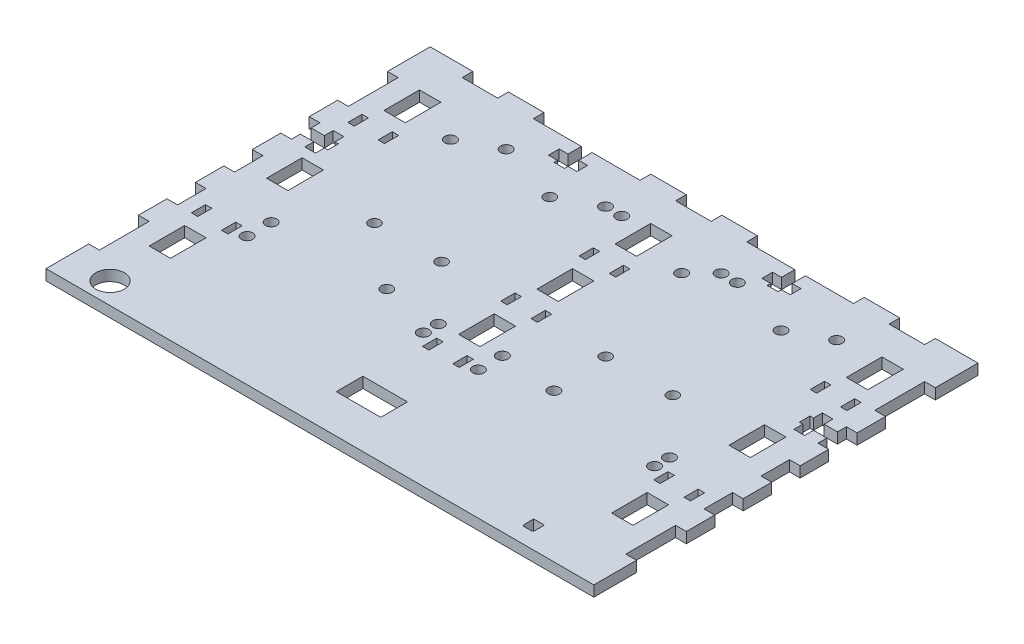
SolidWorks part; units mm, degrees
material "Balsa"
ref_plane "Alzado" through (0, 0, 0) normal (0, 0, 1) x (1, 0, 0)
ref_plane "Planta" through (0, 0, 0) normal (0, 1, 0) x (1, 0, 0)
ref_plane "Vista lateral" through (0, 0, 0) normal (1, 0, 0) x (0, 0, -1)
sketch "Croquis1" plane through (0, 0, 0) normal (0, 1, 0) x (1, 0, 0)
  line L0 (-77, 0) -> (-74, 0) construction
  line L1 (-77, -54) -> (77, -54)
  line L2 (-77, -54) -> (-77, 54)
  line L3 (-77, 54) -> (77, 54)
  line L4 (77, -54) -> (77, 54)
  line L5 (-77, -54) -> (77, 54) construction
  line L6 (-77, 54) -> (77, -54) construction
  line L7 (0, -54) -> (0, 54) construction
  line L8 (-74, 54) -> (-74, -54) construction
  line L9 (-77, -42) -> (-74, -42)
  line L10 (-77, 4) -> (-74, 4)
  line L11 (-77, 4) -> (-77, -4)
  line L12 (-77, -4) -> (-74, -4)
  line L13 (-74, 4) -> (-74, -4)
  line L14 (-77, 12) -> (-74, 12)
  line L15 (-77, 12) -> (-77, 20)
  line L16 (-77, 20) -> (-74, 20)
  line L17 (-74, 12) -> (-74, 20)
  line L22 (-77, 28) -> (-74, 28)
  line L23 (-77, 28) -> (-77, 42)
  line L24 (-77, 42) -> (-74, 42)
  line L25 (-74, 28) -> (-74, 42)
  line L26 (-74, -28) -> (-74, -42)
  line L27 (-77, -28) -> (-74, -28)
  line L28 (-77, -28) -> (-77, -42)
  line L29 (-77, -20) -> (-74, -20)
  line L30 (-74, -12) -> (-74, -20)
  line L31 (-77, -12) -> (-74, -12)
  line L32 (-77, -12) -> (-77, -20)
  line L33 (77, 42) -> (74, 42)
  line L34 (74, 28) -> (74, 42)
  line L35 (77, 28) -> (74, 28)
  line L36 (77, 28) -> (77, 42)
  line L37 (77, -28) -> (77, -42)
  line L38 (77, -28) -> (74, -28)
  line L39 (74, -28) -> (74, -42)
  line L40 (77, -42) -> (74, -42)
  line L41 (77, -12) -> (77, -20)
  line L42 (77, -12) -> (74, -12)
  line L43 (74, -12) -> (74, -20)
  line L44 (77, -20) -> (74, -20)
  line L45 (77, 20) -> (74, 20)
  line L46 (74, 12) -> (74, 20)
  line L47 (77, 12) -> (74, 12)
  line L48 (77, 12) -> (77, 20)
  line L49 (77, -4) -> (74, -4)
  line L50 (74, 4) -> (74, -4)
  line L51 (77, 4) -> (74, 4)
  line L52 (77, 4) -> (77, -4)
  line L53 (-77, 51) -> (77, 51) construction
  line L54 (-55, 51) -> (-65, 51)
  line L55 (-5, 54) -> (5, 54)
  line L56 (-5, 54) -> (-5, 51)
  line L57 (-5, 51) -> (5, 51)
  line L58 (5, 54) -> (5, 51)
  line L59 (15, 54) -> (45, 54)
  line L60 (15, 54) -> (15, 51)
  line L61 (15, 51) -> (45, 51)
  line L62 (45, 54) -> (45, 51)
  line L63 (55, 54) -> (65, 54)
  line L64 (55, 54) -> (55, 51)
  line L65 (55, 51) -> (65, 51)
  line L66 (65, 54) -> (65, 51)
  line L67 (-65, 54) -> (-65, 51)
  line L68 (-55, 54) -> (-65, 54)
  line L69 (-55, 54) -> (-55, 51)
  line L70 (-15, 51) -> (-45, 51)
  line L71 (-45, 54) -> (-45, 51)
  line L72 (-15, 54) -> (-45, 54)
  line L73 (-15, 54) -> (-15, 51)
  line L74 (-77, -48) -> (77, -48) construction
  line L75 (-30, 51) -> (-30, 10.4132) construction
  line L76 (53, -49.6) -> (55, -49.6)
  line L77 (52.5, -49.1) -> (52.5, -46.4)
  line L78 (52.5, -46.4) -> (55.5, -46.4)
  line L79 (55.5, -49.1) -> (55.5, -46.4)
  line L80 (52.5, -49.6) -> (55.5, -46.4) construction
  line L81 (52.5, -46.4) -> (55.5, -49.6) construction
  line L83 (-74, 1.5) -> (-74, -1.5)
  line L90 (-31.5, 51) -> (-28.5, 51)
  line L91 (-31.5, 51) -> (-31.5, 43.27)
  line L92 (-31.5, 43.27) -> (-28.5, 43.27)
  line L93 (-28.5, 51) -> (-28.5, 43.27)
  line L94 (-34, 47.25) -> (-26, 47.25)
  line L95 (-34, 47.25) -> (-34, 44.25)
  line L96 (-34, 44.25) -> (-26, 44.25)
  line L97 (-26, 47.25) -> (-26, 44.25)
  line L98 (31.5, 43.27) -> (28.5, 43.27)
  line L99 (28.5, 51) -> (28.5, 43.27)
  line L100 (31.5, 51) -> (28.5, 51)
  line L101 (31.5, 51) -> (31.5, 43.27)
  line L102 (34, 44.25) -> (26, 44.25)
  line L103 (26, 47.25) -> (26, 44.25)
  line L104 (34, 47.25) -> (26, 47.25)
  line L105 (34, 47.25) -> (34, 44.25)
  line L109 (74, 1.5) -> (74, -1.5)
  line L114 (-74, 16) -> (74, 16) construction
  line L115 (70.25, 12) -> (67.25, 12)
  line L116 (-74, 14.5) -> (-66.27, 14.5)
  line L117 (-74, 14.5) -> (-74, 17.5)
  line L118 (-74, 17.5) -> (-66.27, 17.5)
  line L119 (-66.27, 14.5) -> (-66.27, 17.5)
  line L120 (-70.25, 20) -> (-67.25, 20)
  line L121 (-70.25, 20) -> (-70.25, 12)
  line L122 (-70.25, 12) -> (-67.25, 12)
  line L123 (-67.25, 20) -> (-67.25, 12)
  line L124 (67.25, 20) -> (67.25, 12)
  line L125 (70.25, 20) -> (67.25, 20)
  line L126 (70.25, 20) -> (70.25, 12)
  line L127 (74, 17.5) -> (66.27, 17.5)
  line L128 (66.27, 14.5) -> (66.27, 17.5)
  line L129 (74, 14.5) -> (66.27, 14.5)
  line L130 (74, 14.5) -> (74, 17.5)
  line L131 (74, 0) -> (77, 0) construction
  circle A0 centre (-65, -48) radius 4
  arc A1 (55.5, -49.1) -> (55, -49.6) centre (55, -49.1) cw
  arc A2 (53, -49.6) -> (52.5, -49.1) centre (53, -49.1) cw
  point P0 (0, 0)
  point P78 (54, -48)
  point P123 (-75.5, 4)
  dimension "D17" = 8
  dimension "D22" = 0.5
  dimension "D1" = 108
  dimension "D2" = 154
  dimension "D3" = 3
  dimension "D4" = 4
  dimension "D5" = 3
  dimension "D6" = 8
  dimension "D7" = 8
  dimension "D8" = 8
  dimension "D9" = 14
  dimension "D10" = 3
  dimension "D11" = 5
  dimension "D12" = 10
  dimension "D13" = 10
  dimension "D14" = 30
  dimension "D15" = 10
  dimension "D16" = 10
  dimension "D18" = 6
  dimension "D19" = 23
  dimension "D20" = 3.2
  dimension "D21" = 3
  dimension "D23" = 12
  dimension "D31" = 3
  dimension "D32" = 8
  dimension "D33" = 1.5
  dimension "D34" = 4
  dimension "D35" = 0.98
  dimension "D36" = 7.73
  dimension "D37" = 8
  dimension "D38" = 3
  dimension "D39" = 1.5
  dimension "D40" = 0.98
  dimension "D41" = 8
  dimension "D42" = 4
  dimension "D43" = 3
  dimension "D44" = 7.73
extrude "Saliente-Extruir1" add sketch "Croquis1" along normal mid plane 3
sketch "Croquis2" plane through (0, 1.5, 0) normal (0, 1, 0) x (1, 0, 0)
  line L0 (-4.25, 26) -> (4.25, 26) construction
  line L17 (3, 15) -> (8.9055, 15) construction
  line L18 (-60.75, -18) -> (-69.25, -18) construction
  line L19 (-3, 42) -> (3, 42)
  line L20 (-3, 42) -> (-3, 32)
  line L21 (-3, 32) -> (3, 32)
  line L22 (3, 42) -> (3, 32)
  line L35 (-3, 20) -> (-3, 10)
  line L36 (-3, 20) -> (3, 20)
  line L37 (3, 20) -> (3, 10)
  line L38 (-3, 10) -> (3, 10)
  line L39 (-3, -2) -> (-3, -12)
  line L40 (-3, -2) -> (3, -2)
  line L41 (3, -2) -> (3, -12)
  line L42 (-3, -12) -> (3, -12)
  line L43 (0, -12) -> (0, 42) construction
  line L44 (3.35, 24) -> (5.15, 24)
  line L45 (3.35, 24) -> (3.35, 28)
  line L62 (77, 42) -> (77, 54) construction
  line L63 (62, 42) -> (68, 42)
  line L64 (62, 42) -> (62, 32)
  line L65 (62, 32) -> (68, 32)
  line L66 (68, 42) -> (68, 32)
  line L67 (3.35, 28) -> (5.15, 28)
  line L84 (0, 0) -> (0, -8.6841) construction
  line L93 (-62, 32) -> (-68, 32)
  line L94 (-68, 42) -> (-68, 32)
  line L95 (-62, 42) -> (-68, 42)
  line L96 (-62, 42) -> (-62, 32)
  line L97 (77, 42) -> (74, 42) construction
  line L98 (5.15, 24) -> (5.15, 28)
  line L99 (3.35, 24) -> (5.15, 28) construction
  line L100 (3.35, 28) -> (5.15, 24) construction
  line L101 (-3.35, 24) -> (-5.15, 24)
  line L102 (-3.35, 24) -> (-3.35, 28)
  line L103 (-3.35, 28) -> (-5.15, 28)
  line L104 (-5.15, 24) -> (-5.15, 28)
  line L105 (-3.35, 24) -> (-5.15, 28) construction
  line L106 (-3.35, 28) -> (-5.15, 24) construction
  line L107 (-3.35, 2) -> (-5.15, 6) construction
  line L108 (-3.35, 6) -> (-5.15, 2) construction
  line L109 (3.35, 2) -> (5.15, 6) construction
  line L110 (3.35, 6) -> (5.15, 2) construction
  line L111 (-4.25, 4) -> (4.25, 4) construction
  line L112 (-5.15, 6) -> (-5.15, 2)
  line L113 (-3.35, 2) -> (-5.15, 2)
  line L114 (-3.35, 6) -> (-3.35, 2)
  line L115 (-3.35, 6) -> (-5.15, 6)
  line L116 (5.15, 6) -> (5.15, 2)
  line L117 (3.35, 2) -> (5.15, 2)
  line L118 (3.35, 6) -> (3.35, 2)
  line L119 (3.35, 6) -> (5.15, 6)
  line L120 (3, -7) -> (13.1268, -7) construction
  line L121 (-4.25, -18) -> (4.25, -18) construction
  line L122 (3.35, -20) -> (5.15, -16) construction
  line L123 (3.35, -16) -> (5.15, -20) construction
  line L124 (-3.35, -20) -> (-5.15, -16) construction
  line L125 (-3.35, -16) -> (-5.15, -20) construction
  line L126 (3.35, -20) -> (5.15, -20)
  line L127 (3.35, -20) -> (3.35, -16)
  line L128 (3.35, -16) -> (5.15, -16)
  line L129 (5.15, -20) -> (5.15, -16)
  line L130 (-3.35, -20) -> (-5.15, -20)
  line L131 (-3.35, -20) -> (-3.35, -16)
  line L132 (-3.35, -16) -> (-5.15, -16)
  line L133 (-5.15, -20) -> (-5.15, -16)
  line L134 (-62, 37) -> (-3, 37) construction
  line L135 (-3, 37) -> (3, 37) construction
  line L136 (3, 37) -> (62, 37) construction
  line L137 (-32.5, 37) -> (-32.5, -41.0641) construction
  line L138 (-61.65, 28) -> (-59.85, 24) construction
  line L139 (-61.65, 24) -> (-59.85, 28) construction
  line L140 (-68.35, 28) -> (-70.15, 24) construction
  line L141 (-68.35, 24) -> (-70.15, 28) construction
  line L142 (-65, -12) -> (-65, 42) construction
  line L143 (-60.75, 26) -> (-69.25, 26) construction
  line L144 (-59.85, 24) -> (-59.85, 28)
  line L145 (-61.65, 28) -> (-59.85, 28)
  line L146 (-61.65, 24) -> (-61.65, 28)
  line L147 (-61.65, 24) -> (-59.85, 24)
  line L148 (-70.15, 24) -> (-70.15, 28)
  line L149 (-68.35, 28) -> (-70.15, 28)
  line L150 (-68.35, 24) -> (-68.35, 28)
  line L151 (-68.35, 24) -> (-70.15, 24)
  line L152 (60.75, 26) -> (69.25, 26) construction
  line L153 (65, -12) -> (65, 42) construction
  line L154 (68.35, 24) -> (70.15, 28) construction
  line L155 (68.35, 28) -> (70.15, 24) construction
  line L156 (61.65, 24) -> (59.85, 28) construction
  line L157 (61.65, 28) -> (59.85, 24) construction
  line L158 (68.35, 24) -> (70.15, 24)
  line L159 (68.35, 24) -> (68.35, 28)
  line L160 (68.35, 28) -> (70.15, 28)
  line L161 (70.15, 24) -> (70.15, 28)
  line L162 (61.65, 24) -> (59.85, 24)
  line L163 (61.65, 24) -> (61.65, 28)
  line L164 (61.65, 28) -> (59.85, 28)
  line L165 (59.85, 24) -> (59.85, 28)
  line L166 (-4.25, 4) -> (-65, 4) construction
  line L167 (-3, -7) -> (-65, -7) construction
  line L168 (-68, -1) -> (-62, -1)
  line L169 (-68, -1) -> (-68, 9)
  line L170 (-68, 9) -> (-62, 9)
  line L171 (-62, -1) -> (-62, 9)
  line L172 (-68, -1) -> (-62, 9) construction
  line L173 (-68, 9) -> (-62, -1) construction
  line L174 (61.65, -20) -> (59.85, -16) construction
  line L179 (61.65, -16) -> (59.85, -20) construction
  line L180 (68.35, -20) -> (70.15, -16) construction
  line L181 (68.35, -16) -> (70.15, -20) construction
  line L186 (-68.35, -16) -> (-70.15, -20) construction
  line L187 (-68.35, -20) -> (-70.15, -16) construction
  line L188 (-61.65, -16) -> (-59.85, -20) construction
  line L189 (-61.65, -20) -> (-59.85, -16) construction
  line L190 (-68.35, -16) -> (-70.15, -16)
  line L191 (-68.35, -16) -> (-68.35, -20)
  line L192 (-68.35, -20) -> (-70.15, -20)
  line L193 (-70.15, -16) -> (-70.15, -20)
  line L194 (-61.65, -16) -> (-59.85, -16)
  line L195 (-61.65, -16) -> (-61.65, -20)
  line L196 (-61.65, -20) -> (-59.85, -20)
  line L197 (-59.85, -16) -> (-59.85, -20)
  line L198 (-62, -34) -> (-62, -24)
  line L199 (-62, -34) -> (-68, -34)
  line L200 (-68, -34) -> (-68, -24)
  line L201 (-62, -24) -> (-68, -24)
  line L202 (68, 9) -> (62, -1) construction
  line L203 (68, -1) -> (62, 9) construction
  line L204 (60.75, -18) -> (69.25, -18) construction
  line L205 (62, -24) -> (68, -24)
  line L206 (68, -34) -> (68, -24)
  line L207 (62, -34) -> (68, -34)
  line L208 (62, -34) -> (62, -24)
  line L209 (59.85, -16) -> (59.85, -20)
  line L210 (61.65, -20) -> (59.85, -20)
  line L211 (61.65, -16) -> (61.65, -20)
  line L212 (61.65, -16) -> (59.85, -16)
  line L213 (70.15, -16) -> (70.15, -20)
  line L214 (68.35, -20) -> (70.15, -20)
  line L215 (68.35, -16) -> (68.35, -20)
  line L216 (68.35, -16) -> (70.15, -16)
  line L217 (62, -1) -> (62, 9)
  line L218 (68, 9) -> (62, 9)
  line L219 (68, -1) -> (68, 9)
  line L220 (68, -1) -> (62, -1)
  point P9 (0, 26)
  point P39 (0, 4)
  point P53 (0, -18)
  point P78 (-65, 26)
  point P92 (65, 26)
  point P132 (-65, -18)
  point P140 (65, -18)
  dimension "D10" = 4
  dimension "D2" = 0
  dimension "D4" = 0
  dimension "D5" = 6
  dimension "D6" = 8.5
  dimension "D7" = 3
  dimension "D8" = 1.8
  dimension "D9" = 1.8
  dimension "D11" = 4
  dimension "D12" = 6
  dimension "D13" = 12
  dimension "D14" = 10
  dimension "D15" = 10
  dimension "D16" = 6
  dimension "D34" = 6
  dimension "D35" = 10
  dimension "D36" = 9
extrude "Cortar-Extruir1" cut sketch "Croquis2" against normal blind 3
sketch "Croquis3" plane through (0, 1.5, 0) normal (0, 1, 0) x (1, 0, 0)
  line L0 (52.5, -46.4) -> (0, -46.4) construction
  line L1 (0, -46.4) -> (0, -39.4) construction
  line L3 (-6.25, -43.15) -> (6.25, -43.15)
  line L4 (-6.25, -43.15) -> (-6.25, -35.65)
  line L5 (-6.25, -35.65) -> (6.25, -35.65)
  line L6 (6.25, -43.15) -> (6.25, -35.65)
  line L7 (-6.25, -43.15) -> (6.25, -35.65) construction
  line L8 (-6.25, -35.65) -> (6.25, -43.15) construction
  dimension "D1" = 7.5
  dimension "D2" = 12.5
  dimension "D3" = 7
extrude "Cortar-Extruir2" cut sketch "Croquis3" against normal blind 10
sketch "Croquis4" plane through (0, 1.5, 0) normal (0, 1, 0) x (1, 0, 0)
  circle A0 centre (-41.39, 39.73) radius 1.5875
  circle A1 centre (-13.45, 39.73) radius 1.5875
  circle A2 centre (51.55, 39.73) radius 1.5875
  circle A3 centre (23.61, 39.73) radius 1.5875
  circle A4 centre (56.63, -12.34) radius 1.5875
  circle A5 centre (8.37, -11.07) radius 1.5875
  circle A6 centre (-8.37, -12.34) radius 1.5875
  circle A7 centre (-56.63, -11.07) radius 1.5875
  circle A8 centre (-24.13, -11.07) radius 1.5875
  circle A9 centre (24.13, -12.34) radius 1.5875
  circle A10 centre (19.05, 39.73) radius 1.5875
  circle A11 centre (-8.89, 39.73) radius 1.5875
extrude "Cortar-Extruir3" cut sketch "Croquis4" against normal blind 10
sketch "Croquis5" plane through (0, 1.5, 0) normal (0, 1, 0) x (1, 0, 0)
  line L0 (-5.15, -18) -> (-59.85, -18) construction
  line L1 (-53, 41.27) -> (-12, 41.27) construction
  line L2 (-53, 41.27) -> (-53, -34.73) construction
  line L3 (-53, -34.73) -> (-12, -34.73) construction
  line L4 (-12, 41.27) -> (-12, -34.73) construction
  line L5 (-53, 41.27) -> (-12, -34.73) construction
  line L6 (-53, -34.73) -> (-12, 41.27) construction
  line L7 (-5.15, -16) -> (-5.15, -20) construction
  line L8 (-59.85, -20) -> (-59.85, -16) construction
  line L9 (-32.5, -18) -> (-32.5, 43.27) construction
  line L10 (-32.5, 43.27) -> (-31.5, 43.27) construction
  line L11 (-31.5, 43.27) -> (-28.5, 43.27) construction
  line L12 (-41.925, 3.27) -> (-23.075, 3.27) construction
  line L13 (0, 0) -> (0, 17.3029) construction
  line L14 (41.925, 3.27) -> (23.075, 3.27) construction
  circle A0 centre (-41.925, 3.27) radius 1.55
  circle A1 centre (-23.075, 3.27) radius 1.55
  circle A2 centre (23.075, 3.27) radius 1.55
  circle A3 centre (41.925, 3.27) radius 1.55
  point P0 (-32.5, 3.27)
  point P19 (-30, 43.27)
  point P23 (-32.5, 3.27)
  point P30 (32.5, 3.27)
  dimension "D5" = 3.1
  dimension "D1" = 76
  dimension "D2" = 41
  dimension "D3" = 2
  dimension "D4" = 18.85
extrude "Cortar-Extruir4" cut sketch "Croquis5" against normal blind 10
sketch "Croquis6" plane through (0, -1.5, 0) normal (0, -1, 0) x (1, 0, 0)
  circle A0 centre (-51.55, -34.24) radius 1.5875
  circle A1 centre (-23.61, -34.24) radius 1.5748
  circle A2 centre (13.45, -34.24) radius 1.5875
  circle A3 centre (41.39, -34.24) radius 1.5875
  circle A4 centre (56.63, 16.56) radius 1.5875
  circle A5 centre (8.37, 17.83) radius 1.5875
  circle A6 centre (-56.63, 17.83) radius 1.5875
  circle A7 centre (-8.37, 16.56) radius 1.5875
extrude "Cortar-Extruir5" cut sketch "Croquis6" against normal blind 10
sketch "Croquis7" plane through (0, 1.5, 0) normal (0, 1, 0) x (1, 0, 0)
  line L0 (-65, 32) -> (-65, 42) construction
  line L3 (-68, 32) -> (-62, 32) construction
  line L4 (-62, 42) -> (-68, 42) construction
  line L5 (-4.9598, 37.15) -> (4.9598, 37.15)
  line L6 (-69.9598, 36.85) -> (-60.0402, 36.85)
  line L7 (-69.9598, 36.85) -> (-69.9598, 37.15)
  line L8 (-69.9598, 37.15) -> (-60.0402, 37.15)
  line L9 (-60.0402, 36.85) -> (-60.0402, 37.15)
  line L10 (-69.9598, 36.85) -> (-60.0402, 37.15) construction
  line L11 (-69.9598, 37.15) -> (-60.0402, 36.85) construction
  line L12 (-65.15, 30.0862) -> (-64.85, 30.0862)
  line L13 (-65.15, 30.0862) -> (-65.15, 43.9138)
  line L14 (-65.15, 43.9138) -> (-64.85, 43.9138)
  line L15 (-64.85, 30.0862) -> (-64.85, 43.9138)
  line L16 (-65.15, 30.0862) -> (-64.85, 43.9138) construction
  line L17 (-65.15, 43.9138) -> (-64.85, 30.0862) construction
  line L18 (-4.9598, 36.85) -> (4.9598, 36.85)
  line L19 (-0.15, 30.0862) -> (-0.15, 43.9138)
  line L20 (0.15, 30.0862) -> (0.15, 43.9138)
  line L21 (60.0402, 37.15) -> (69.9598, 37.15)
  line L22 (60.0402, 36.85) -> (69.9598, 36.85)
  line L23 (64.85, 30.0862) -> (64.85, 43.9138)
  line L24 (65.15, 30.0862) -> (65.15, 43.9138)
  line L25 (-4.9598, 15.15) -> (4.9598, 15.15)
  line L26 (-4.9598, 14.85) -> (4.9598, 14.85)
  line L27 (-0.15, 8.0862) -> (-0.15, 21.9138)
  line L28 (0.15, 8.0862) -> (0.15, 21.9138)
  line L29 (-69.7947, 4.4135) -> (-59.8752, 4.4135)
  line L30 (-69.7947, 4.1135) -> (-59.8752, 4.1135)
  line L31 (-64.985, -2.6503) -> (-64.985, 11.1773)
  line L32 (-64.685, -2.6503) -> (-64.685, 11.1773)
  line L33 (-4.9598, -6.85) -> (4.9598, -6.85)
  line L34 (-4.9598, -7.15) -> (4.9598, -7.15)
  line L35 (-0.15, -13.9138) -> (-0.15, -0.0862)
  line L36 (0.15, -13.9138) -> (0.15, -0.0862)
  line L37 (59.6021, 4.0258) -> (69.5216, 4.0258)
  line L38 (59.6021, 3.7258) -> (69.5216, 3.7258)
  line L39 (64.4118, -3.038) -> (64.4118, 10.7896)
  line L40 (64.7118, -3.038) -> (64.7118, 10.7896)
  line L45 (60.0402, -28.85) -> (69.9598, -28.85)
  line L46 (60.0402, -29.15) -> (69.9598, -29.15)
  line L47 (64.85, -35.9138) -> (64.85, -22.0862)
  line L48 (65.15, -35.9138) -> (65.15, -22.0862)
  line L57 (-69.9598, -28.85) -> (-60.0402, -28.85)
  line L58 (-69.9598, -29.15) -> (-60.0402, -29.15)
  line L59 (-65.15, -35.9138) -> (-65.15, -22.0862)
  line L60 (-64.85, -35.9138) -> (-64.85, -22.0862)
  line L61 (-69.9598, 15.15) -> (-60.0402, 15.15)
  line L62 (-69.9598, 14.85) -> (-60.0402, 14.85)
  line L63 (-65.15, 8.0862) -> (-65.15, 21.9138)
  line L64 (-64.85, 8.0862) -> (-64.85, 21.9138)
  line L65 (-69.9598, -6.85) -> (-60.0402, -6.85)
  line L66 (-69.9598, -7.15) -> (-60.0402, -7.15)
  line L67 (-65.15, -13.9138) -> (-65.15, -0.0862)
  line L68 (-64.85, -13.9138) -> (-64.85, -0.0862)
  line L69 (-4.9598, -28.85) -> (4.9598, -28.85)
  line L70 (-4.9598, -29.15) -> (4.9598, -29.15)
  line L71 (-0.15, -35.9138) -> (-0.15, -22.0862)
  line L72 (0.15, -35.9138) -> (0.15, -22.0862)
  line L73 (60.0402, 15.15) -> (69.9598, 15.15)
  line L74 (60.0402, 14.85) -> (69.9598, 14.85)
  line L75 (64.85, 8.0862) -> (64.85, 21.9138)
  line L76 (65.15, 8.0862) -> (65.15, 21.9138)
  line L77 (60.0402, -6.85) -> (69.9598, -6.85)
  line L78 (60.0402, -7.15) -> (69.9598, -7.15)
  line L79 (64.85, -13.9138) -> (64.85, -0.0862)
  line L80 (65.15, -13.9138) -> (65.15, -0.0862)
  point P6 (-65, 37)
  point P11 (-65, 37)
  dimension "D1" = 0.3
  dimension "D2" = 0.3
  dimension "D3" = 3
  dimension "D4" = 4
sketch "Croquis8" plane through (0, 1.5, 0) normal (0, 1, 0) x (1, 0, 0)
  line L0 (-60.9976, 22.6864) -> (-60.9976, 25.9114)
  line L2 (-69.4235, 22.5308) -> (-69.4235, 25.7558)
  line L4 (-69.1235, 22.5308) -> (-69.1235, 25.7558)
  line L5 (-6.6732, 26.0558) -> (-4.4235, 26.0558)
  line L6 (-69.1235, 25.7558) -> (-66.8737, 25.7558)
  line L7 (-71.6732, 25.7558) -> (-69.4235, 25.7558)
  line L9 (-71.6732, 26.0558) -> (-69.4235, 26.0558)
  line L11 (-6.6732, 25.7558) -> (-4.4235, 25.7558)
  line L12 (-4.4235, 26.0558) -> (-4.4235, 29.2808)
  line L13 (-60.6976, 22.6864) -> (-60.6976, 25.9114)
  line L14 (-69.4235, 26.0558) -> (-69.4235, 29.2808)
  line L15 (-60.6976, 25.9114) -> (-58.4479, 25.9114)
  line L16 (-63.2474, 25.9114) -> (-60.9976, 25.9114)
  line L17 (-63.2474, 26.2114) -> (-60.9976, 26.2114)
  line L18 (-4.1235, 26.0558) -> (-4.1235, 29.2808)
  line L20 (-60.9976, 26.052) -> (-60.9976, 26.0708)
  line L21 (-69.1235, 26.0558) -> (-69.1235, 29.2808)
  line L22 (-60.6976, 26.052) -> (-60.6976, 26.0708)
  line L23 (-60.6976, 26.2114) -> (-60.6976, 29.4364)
  line L24 (-60.9976, 26.2114) -> (-60.9976, 29.4364)
  line L25 (-60.6976, 26.2114) -> (-58.4479, 26.2114)
  line L26 (-69.1235, 26.0558) -> (-66.8737, 26.0558)
  line L28 (-4.1235, 26.0558) -> (-1.8737, 26.0558)
  line L29 (-4.1235, 25.7558) -> (-1.8737, 25.7558)
  line L30 (-4.1235, 22.5308) -> (-4.1235, 25.7558)
  line L31 (-4.4235, 22.5308) -> (-4.4235, 25.7558)
  line L32 (1.7526, 26.2114) -> (4.0024, 26.2114)
  line L33 (1.7526, 25.9114) -> (4.0024, 25.9114)
  line L34 (4.0024, 26.2114) -> (4.0024, 29.4364)
  line L35 (4.3024, 26.2114) -> (4.3024, 29.4364)
  line L36 (4.3024, 26.2114) -> (6.5521, 26.2114)
  line L37 (4.3024, 25.9114) -> (6.5521, 25.9114)
  line L38 (4.3024, 22.6864) -> (4.3024, 25.9114)
  line L39 (4.0024, 22.6864) -> (4.0024, 25.9114)
  line L40 (58.3268, 26.0558) -> (60.5765, 26.0558)
  line L41 (58.3268, 25.7558) -> (60.5765, 25.7558)
  line L42 (60.5765, 26.0558) -> (60.5765, 29.2808)
  line L43 (60.8765, 26.0558) -> (60.8765, 29.2808)
  line L44 (60.8765, 26.0558) -> (63.1263, 26.0558)
  line L45 (60.8765, 25.7558) -> (63.1263, 25.7558)
  line L46 (60.8765, 22.5308) -> (60.8765, 25.7558)
  line L47 (60.5765, 22.5308) -> (60.5765, 25.7558)
  line L48 (66.7526, 26.2114) -> (69.0024, 26.2114)
  line L49 (66.7526, 25.9114) -> (69.0024, 25.9114)
  line L50 (69.0024, 26.2114) -> (69.0024, 29.4364)
  line L51 (69.3024, 26.2114) -> (69.3024, 29.4364)
  line L52 (69.3024, 26.2114) -> (71.5521, 26.2114)
  line L53 (69.3024, 25.9114) -> (71.5521, 25.9114)
  line L54 (69.3024, 22.6864) -> (69.3024, 25.9114)
  line L55 (69.0024, 22.6864) -> (69.0024, 25.9114)
  line L56 (-6.6732, 4.0558) -> (-4.4235, 4.0558)
  line L57 (-6.6732, 3.7558) -> (-4.4235, 3.7558)
  line L58 (-4.4235, 4.0558) -> (-4.4235, 7.2808)
  line L59 (-4.1235, 4.0558) -> (-4.1235, 7.2808)
  line L60 (-4.1235, 4.0558) -> (-1.8737, 4.0558)
  line L61 (-4.1235, 3.7558) -> (-1.8737, 3.7558)
  line L62 (-4.1235, 0.5308) -> (-4.1235, 3.7558)
  line L63 (-4.4235, 0.5308) -> (-4.4235, 3.7558)
  line L64 (1.7526, 4.2114) -> (4.0024, 4.2114)
  line L65 (1.7526, 3.9114) -> (4.0024, 3.9114)
  line L66 (4.0024, 4.2114) -> (4.0024, 7.4364)
  line L67 (4.3024, 4.2114) -> (4.3024, 7.4364)
  line L68 (4.3024, 4.2114) -> (6.5521, 4.2114)
  line L69 (4.3024, 3.9114) -> (6.5521, 3.9114)
  line L70 (4.3024, 0.6864) -> (4.3024, 3.9114)
  line L71 (4.0024, 0.6864) -> (4.0024, 3.9114)
  line L88 (-6.6732, -17.9442) -> (-4.4235, -17.9442)
  line L89 (-6.6732, -18.2442) -> (-4.4235, -18.2442)
  line L90 (-4.4235, -17.9442) -> (-4.4235, -14.7192)
  line L91 (-4.1235, -17.9442) -> (-4.1235, -14.7192)
  line L92 (-4.1235, -17.9442) -> (-1.8737, -17.9442)
  line L93 (-4.1235, -18.2442) -> (-1.8737, -18.2442)
  line L94 (-4.1235, -21.4692) -> (-4.1235, -18.2442)
  line L95 (-4.4235, -21.4692) -> (-4.4235, -18.2442)
  line L96 (1.7526, -17.7886) -> (4.0024, -17.7886)
  line L97 (1.7526, -18.0886) -> (4.0024, -18.0886)
  line L98 (4.0024, -17.7886) -> (4.0024, -14.5636)
  line L99 (4.3024, -17.7886) -> (4.3024, -14.5636)
  line L100 (4.3024, -17.7886) -> (6.5521, -17.7886)
  line L101 (4.3024, -18.0886) -> (6.5521, -18.0886)
  line L102 (4.3024, -21.3136) -> (4.3024, -18.0886)
  line L103 (4.0024, -21.3136) -> (4.0024, -18.0886)
  line L104 (58.3268, -17.9442) -> (60.5765, -17.9442)
  line L105 (58.3268, -18.2442) -> (60.5765, -18.2442)
  line L106 (60.5765, -17.9442) -> (60.5765, -14.7192)
  line L107 (60.8765, -17.9442) -> (60.8765, -14.7192)
  line L108 (60.8765, -17.9442) -> (63.1263, -17.9442)
  line L109 (60.8765, -18.2442) -> (63.1263, -18.2442)
  line L110 (60.8765, -21.4692) -> (60.8765, -18.2442)
  line L111 (60.5765, -21.4692) -> (60.5765, -18.2442)
  line L112 (66.7526, -17.7886) -> (69.0024, -17.7886)
  line L113 (66.7526, -18.0886) -> (69.0024, -18.0886)
  line L114 (69.0024, -17.7886) -> (69.0024, -14.5636)
  line L115 (69.3024, -17.7886) -> (69.3024, -14.5636)
  line L116 (69.3024, -17.7886) -> (71.5521, -17.7886)
  line L117 (69.3024, -18.0886) -> (71.5521, -18.0886)
  line L118 (69.3024, -21.3136) -> (69.3024, -18.0886)
  line L119 (69.0024, -21.3136) -> (69.0024, -18.0886)
  line L136 (-71.6732, -17.9442) -> (-69.4235, -17.9442)
  line L137 (-71.6732, -18.2442) -> (-69.4235, -18.2442)
  line L138 (-69.4235, -17.9442) -> (-69.4235, -14.7192)
  line L139 (-69.1235, -17.9442) -> (-69.1235, -14.7192)
  line L140 (-69.1235, -17.9442) -> (-66.8737, -17.9442)
  line L141 (-69.1235, -18.2442) -> (-66.8737, -18.2442)
  line L142 (-69.1235, -21.4692) -> (-69.1235, -18.2442)
  line L143 (-69.4235, -21.4692) -> (-69.4235, -18.2442)
  line L144 (-63.2474, -17.7886) -> (-60.9976, -17.7886)
  line L145 (-63.2474, -18.0886) -> (-60.9976, -18.0886)
  line L146 (-60.9976, -17.7886) -> (-60.9976, -14.5636)
  line L147 (-60.6976, -17.7886) -> (-60.6976, -14.5636)
  line L148 (-60.6976, -17.7886) -> (-58.4479, -17.7886)
  line L149 (-60.6976, -18.0886) -> (-58.4479, -18.0886)
  line L150 (-60.6976, -21.3136) -> (-60.6976, -18.0886)
  line L151 (-60.9976, -21.3136) -> (-60.9976, -18.0886)
  line L152 (-71.6732, 4.0558) -> (-69.4235, 4.0558)
  line L153 (-71.6732, 3.7558) -> (-69.4235, 3.7558)
  line L154 (-69.4235, 4.0558) -> (-69.4235, 7.2808)
  line L155 (-69.1235, 4.0558) -> (-69.1235, 7.2808)
  line L156 (-69.1235, 4.0558) -> (-66.8737, 4.0558)
  line L157 (-69.1235, 3.7558) -> (-66.8737, 3.7558)
  line L158 (-69.1235, 0.5308) -> (-69.1235, 3.7558)
  line L159 (-69.4235, 0.5308) -> (-69.4235, 3.7558)
  line L160 (-63.2474, 4.2114) -> (-60.9976, 4.2114)
  line L161 (-63.2474, 3.9114) -> (-60.9976, 3.9114)
  line L162 (-60.9976, 4.2114) -> (-60.9976, 7.4364)
  line L163 (-60.6976, 4.2114) -> (-60.6976, 7.4364)
  line L164 (-60.6976, 4.2114) -> (-58.4479, 4.2114)
  line L165 (-60.6976, 3.9114) -> (-58.4479, 3.9114)
  line L166 (-60.6976, 0.6864) -> (-60.6976, 3.9114)
  line L167 (-60.9976, 0.6864) -> (-60.9976, 3.9114)
  line L168 (58.3268, 4.0558) -> (60.5765, 4.0558)
  line L169 (58.3268, 3.7558) -> (60.5765, 3.7558)
  line L170 (60.5765, 4.0558) -> (60.5765, 7.2808)
  line L171 (60.8765, 4.0558) -> (60.8765, 7.2808)
  line L172 (60.8765, 4.0558) -> (63.1263, 4.0558)
  line L173 (60.8765, 3.7558) -> (63.1263, 3.7558)
  line L174 (60.8765, 0.5308) -> (60.8765, 3.7558)
  line L175 (60.5765, 0.5308) -> (60.5765, 3.7558)
  line L176 (66.7526, 4.2114) -> (69.0024, 4.2114)
  line L177 (66.7526, 3.9114) -> (69.0024, 3.9114)
  line L178 (69.0024, 4.2114) -> (69.0024, 7.4364)
  line L179 (69.3024, 4.2114) -> (69.3024, 7.4364)
  line L180 (69.3024, 4.2114) -> (71.5521, 4.2114)
  line L181 (69.3024, 3.9114) -> (71.5521, 3.9114)
  line L182 (69.3024, 0.6864) -> (69.3024, 3.9114)
  line L183 (69.0024, 0.6864) -> (69.0024, 3.9114)
  point P0 (-69.2735, 25.9058)
  point P5 (-60.8476, 26.0614)
  dimension "D1" = 0.3
  dimension "D2" = 0.3
  dimension "D3" = 0.3
  dimension "D4" = 0.3
  dimension "D5" = 3
  dimension "D6" = 3
sketch "Croquis9" plane through (0, 1.5, 0) normal (0, 1, 0) x (1, 0, 0)
  line L0 (-0.9321, -38.4602) -> (-0.9321, -32.9525)
  line L2 (-0.9321, -45.8475) -> (-0.9321, -40.3398)
  line L4 (0.9321, -45.8475) -> (0.9321, -40.3398)
  line L5 (-53.4503, 34.5176) -> (-52.6925, 34.5176)
  line L6 (-53.5316, 34.2288) -> (-52.5205, 34.2288)
  line L7 (-10.3133, -40.3398) -> (-0.9321, -40.3398)
  line L9 (-10.3133, -38.4602) -> (-0.9321, -38.4602)
  line L11 (-50.5689, 35.9617) -> (-51.0744, 35.0861)
  line L12 (-50.3594, 35.7469) -> (-50.7383, 35.0907)
  line L13 (-50.5495, 32.5295) -> (-51.055, 33.4051)
  line L14 (-50.8402, 32.4555) -> (-51.2191, 33.1117)
  line L15 (-42.9336, 39.9923) -> (-42.1758, 39.9923)
  line L16 (0.9321, -38.4602) -> (0.9321, -32.9525)
  line L17 (0.9321, -40.3398) -> (10.3133, -40.3398)
  line L18 (-43.0149, 39.7035) -> (-42.0038, 39.7035)
  line L19 (0.9321, -38.4602) -> (10.3133, -38.4602)
  line L20 (-40.0522, 41.4364) -> (-40.5577, 40.5608)
  line L21 (-39.8427, 41.2216) -> (-40.2216, 40.5654)
  line L22 (-40.0328, 38.0042) -> (-40.5383, 38.8798)
  line L23 (-40.3235, 37.9302) -> (-40.7024, 38.5864)
  line L24 (-25.1543, 34.6282) -> (-24.3965, 34.6282)
  line L25 (-25.2356, 34.3394) -> (-24.2245, 34.3394)
  line L26 (-22.2729, 36.0723) -> (-22.7784, 35.1967)
  line L27 (-22.0634, 35.8575) -> (-22.4423, 35.2013)
  line L28 (-22.2535, 32.6401) -> (-22.759, 33.5157)
  line L29 (-22.5442, 32.5661) -> (-22.9231, 33.2224)
  line L30 (-15.0106, 40.2051) -> (-14.2529, 40.2051)
  line L31 (-15.0919, 39.9163) -> (-14.0808, 39.9163)
  line L32 (-12.1292, 41.6492) -> (-12.6348, 40.7736)
  line L33 (-11.9198, 41.4344) -> (-12.2987, 40.7782)
  line L34 (-12.1098, 38.217) -> (-12.6154, 39.0926)
  line L35 (-12.4006, 38.143) -> (-12.7794, 38.7992)
  line L36 (-10.2863, 40.0234) -> (-9.5285, 40.0234)
  line L37 (-10.3675, 39.7346) -> (-9.3564, 39.7346)
  line L38 (-7.4048, 41.4675) -> (-7.9104, 40.5919)
  line L39 (-7.1954, 41.2527) -> (-7.5743, 40.5965)
  line L40 (-7.3854, 38.0353) -> (-7.891, 38.9109)
  line L41 (-7.6762, 37.9613) -> (-8.055, 38.6175)
  line L42 (11.882, 34.6933) -> (12.6398, 34.6933)
  line L43 (11.8008, 34.4045) -> (12.8119, 34.4045)
  line L44 (14.7635, 36.1374) -> (14.2579, 35.2618)
  line L45 (14.9729, 35.9226) -> (14.594, 35.2664)
  line L46 (14.7829, 32.7052) -> (14.2773, 33.5808)
  line L47 (14.4921, 32.6312) -> (14.1132, 33.2874)
  line L48 (17.515, 40.2051) -> (18.2727, 40.2051)
  line L49 (17.4337, 39.9163) -> (18.4448, 39.9163)
  line L50 (20.3964, 41.6492) -> (19.8908, 40.7736)
  line L51 (20.6058, 41.4344) -> (20.2269, 40.7782)
  line L52 (20.4158, 38.217) -> (19.9102, 39.0926)
  line L53 (20.1251, 38.143) -> (19.7462, 38.7992)
  line L54 (21.6942, 39.7205) -> (22.452, 39.7205)
  line L55 (21.613, 39.4317) -> (22.624, 39.4317)
  line L56 (24.5756, 41.1646) -> (24.0701, 40.289)
  line L57 (24.7851, 40.9499) -> (24.4062, 40.2936)
  line L58 (24.5951, 37.7324) -> (24.0895, 38.608)
  line L59 (24.3043, 37.6584) -> (23.9254, 38.3147)
  line L60 (50.0236, 40.1235) -> (50.7814, 40.1235)
  line L61 (49.9423, 39.8348) -> (50.9534, 39.8348)
  line L62 (52.905, 41.5677) -> (52.3995, 40.692)
  line L63 (53.1145, 41.3529) -> (52.7356, 40.6966)
  line L64 (52.9244, 38.1355) -> (52.4189, 39.0111)
  line L65 (52.6337, 38.0614) -> (52.2548, 38.7177)
  line L66 (-1.5048, 0.309) -> (-0.747, 0.309)
  line L67 (-1.5861, 0.0202) -> (-0.575, 0.0202)
  line L68 (1.3766, 1.7531) -> (0.8711, 0.8775)
  line L69 (1.5861, 1.5383) -> (1.2072, 0.8821)
  line L70 (1.396, -1.6791) -> (0.8905, -0.8035)
  line L71 (1.1053, -1.7531) -> (0.7264, -1.0969)
  line L72 (39.9796, 34.4465) -> (40.7374, 34.4465)
  line L73 (39.8983, 34.1577) -> (40.9094, 34.1577)
  line L74 (42.861, 35.8906) -> (42.3555, 35.015)
  line L75 (43.0705, 35.6759) -> (42.6916, 35.0196)
  line L76 (42.8804, 32.4584) -> (42.3749, 33.334)
  line L77 (42.5897, 32.3844) -> (42.2108, 33.0407)
  line L78 (-43.5616, 3.4387) -> (-42.8038, 3.4387)
  line L79 (-43.6429, 3.15) -> (-42.6318, 3.15)
  line L80 (-40.6802, 4.8829) -> (-41.1857, 4.0072)
  line L81 (-40.4707, 4.6681) -> (-40.8496, 4.0118)
  line L82 (-40.6608, 1.4507) -> (-41.1663, 2.3263)
  line L83 (-40.9515, 1.3766) -> (-41.3304, 2.0329)
  line L84 (-24.7269, 3.7396) -> (-23.9691, 3.7396)
  line L85 (-24.8082, 3.4508) -> (-23.7971, 3.4508)
  line L86 (-21.8455, 5.1837) -> (-22.351, 4.3081)
  line L87 (-21.636, 4.969) -> (-22.0149, 4.3127)
  line L88 (-21.8261, 1.7515) -> (-22.3316, 2.6272)
  line L89 (-22.1168, 1.6775) -> (-22.4957, 2.3338)
  line L90 (21.5839, 3.4984) -> (22.3417, 3.4984)
  line L91 (21.5026, 3.2096) -> (22.5137, 3.2096)
  line L92 (24.4653, 4.9425) -> (23.9598, 4.0669)
  line L93 (24.6748, 4.7278) -> (24.2959, 4.0715)
  line L94 (24.4847, 1.5103) -> (23.9792, 2.3859)
  line L95 (24.194, 1.4363) -> (23.8151, 2.0926)
  line L96 (40.2486, 3.6154) -> (41.0064, 3.6154)
  line L97 (40.1673, 3.3266) -> (41.1784, 3.3266)
  line L98 (43.13, 5.0596) -> (42.6244, 4.1839)
  line L99 (43.3394, 4.8448) -> (42.9606, 4.1885)
  line L100 (43.1494, 1.6273) -> (42.6439, 2.503)
  line L101 (42.8587, 1.5533) -> (42.4798, 2.2096)
  line L102 (55.1188, -11.5985) -> (55.8766, -11.5985)
  line L103 (55.0376, -11.8873) -> (56.0487, -11.8873)
  line L104 (58.0003, -10.1543) -> (57.4947, -11.03)
  line L105 (58.2097, -10.3691) -> (57.8308, -11.0254)
  line L106 (58.0197, -13.5866) -> (57.5141, -12.7109)
  line L107 (57.7289, -13.6606) -> (57.35, -13.0043)
  line L108 (54.615, -16.2048) -> (55.3728, -16.2048)
  line L109 (54.5338, -16.4936) -> (55.5448, -16.4936)
  line L110 (57.4964, -14.7607) -> (56.9909, -15.6363)
  line L111 (57.7059, -14.9755) -> (57.327, -15.6317)
  line L112 (57.5158, -18.1929) -> (57.0103, -17.3173)
  line L113 (57.2251, -18.2669) -> (56.8462, -17.6107)
  line L114 (22.4128, -11.9193) -> (23.1706, -11.9193)
  line L115 (22.3316, -12.2081) -> (23.3427, -12.2081)
  line L116 (25.2943, -10.4752) -> (24.7887, -11.3508)
  line L117 (25.5037, -10.69) -> (25.1248, -11.3462)
  line L118 (25.3137, -13.9074) -> (24.8081, -13.0318)
  line L119 (25.0229, -13.9814) -> (24.6441, -13.3252)
  line L120 (6.8815, -10.7684) -> (7.6393, -10.7684)
  line L121 (6.8003, -11.0572) -> (7.8113, -11.0572)
  line L122 (9.7629, -9.3243) -> (9.2574, -10.1999)
  line L123 (9.9724, -9.539) -> (9.5935, -10.1953)
  line L124 (9.7824, -12.7565) -> (9.2768, -11.8809)
  line L125 (9.4916, -12.8305) -> (9.1127, -12.1742)
  line L126 (6.7673, -17.336) -> (7.5251, -17.336)
  line L127 (6.686, -17.6248) -> (7.6971, -17.6248)
  line L128 (9.6487, -15.8919) -> (9.1432, -16.7675)
  line L129 (9.8582, -16.1066) -> (9.4793, -16.7629)
  line L130 (9.6681, -19.3241) -> (9.1626, -18.4485)
  line L131 (9.3774, -19.3981) -> (8.9985, -18.7418)
  line L132 (-25.8681, -10.6407) -> (-25.1104, -10.6407)
  line L133 (-25.9494, -10.9295) -> (-24.9383, -10.9295)
  line L134 (-22.9867, -9.1966) -> (-23.4923, -10.0722)
  line L135 (-22.7773, -9.4114) -> (-23.1561, -10.0676)
  line L136 (-22.9673, -12.6288) -> (-23.4729, -11.7532)
  line L137 (-23.258, -12.7028) -> (-23.6369, -12.0466)
  line L138 (-9.844, -11.9356) -> (-9.0863, -11.9356)
  line L139 (-9.9253, -12.2244) -> (-8.9142, -12.2244)
  line L140 (-6.9626, -10.4915) -> (-7.4682, -11.3671)
  line L141 (-6.7532, -10.7062) -> (-7.1321, -11.3625)
  line L142 (-6.9432, -13.9237) -> (-7.4488, -13.048)
  line L143 (-7.234, -13.9977) -> (-7.6128, -13.3414)
  line L144 (-10.0059, -16.063) -> (-9.2481, -16.063)
  line L145 (-10.0872, -16.3518) -> (-9.0761, -16.3518)
  line L146 (-7.1245, -14.6189) -> (-7.63, -15.4945)
  line L147 (-6.915, -14.8336) -> (-7.2939, -15.4899)
  line L148 (-7.1051, -18.0511) -> (-7.6106, -17.1755)
  line L149 (-7.3958, -18.1251) -> (-7.7747, -17.4688)
  line L150 (-58.2119, -17.5965) -> (-57.4542, -17.5965)
  line L151 (-58.2932, -17.8852) -> (-57.2821, -17.8852)
  line L152 (-55.3305, -16.1523) -> (-55.8361, -17.028)
  line L153 (-55.1211, -16.3671) -> (-55.5, -17.0234)
  line L154 (-55.3111, -19.5845) -> (-55.8167, -18.7089)
  line L155 (-55.6018, -19.6586) -> (-55.9807, -19.0023)
  line L156 (-57.9888, -10.864) -> (-57.231, -10.864)
  line L157 (-58.07, -11.1528) -> (-57.0589, -11.1528)
  line L158 (-55.1073, -9.4199) -> (-55.6129, -10.2955)
  line L159 (-54.8979, -9.6346) -> (-55.2768, -10.2909)
  line L160 (-55.0879, -12.8521) -> (-55.5935, -11.9765)
  line L161 (-55.3787, -12.9261) -> (-55.7576, -12.2698)
  point P0 (0, -39.4)
  point P5 (0, -39.4)
  point P29 (-51.55, 34.24)
  point P39 (-41.0333, 39.7147)
  point P52 (-23.254, 34.3506)
  point P65 (-13.1103, 39.9275)
  point P78 (-8.3859, 39.7458)
  point P91 (13.7824, 34.4157)
  point P104 (19.4153, 39.9275)
  point P117 (23.5946, 39.4429)
  point P130 (51.9239, 39.846)
  point P143 (0.3955, 0.0314)
  point P156 (41.8799, 34.1689)
  point P169 (-41.6613, 3.1612)
  point P182 (-22.8266, 3.462)
  point P195 (23.4842, 3.2208)
  point P208 (42.1489, 3.3378)
  point P221 (57.0192, -11.8761)
  point P234 (56.5153, -16.4824)
  point P247 (24.3132, -12.1969)
  point P260 (8.7819, -11.046)
  point P273 (8.6676, -17.6136)
  point P286 (-23.9678, -10.9183)
  point P299 (-7.9437, -12.2132)
  point P312 (-8.1056, -16.3406)
  point P325 (-56.3116, -17.874)
  point P338 (-56.0884, -11.1416)
  dimension "D1" = 0.3
  dimension "D2" = 3
  dimension "D3" = 0.3
  dimension "D4" = 0.3
  dimension "D5" = 0.3
  dimension "D6" = 0.3
  dimension "D7" = 0.3
  dimension "D8" = 0.3
  dimension "D9" = 0.3
  dimension "D10" = 0.3
  dimension "D11" = 0.3
  dimension "D12" = 0.3
  dimension "D13" = 0.3
  dimension "D14" = 0.3
  dimension "D15" = 0.3
  dimension "D16" = 0.3
  dimension "D17" = 0.3
  dimension "D18" = 0.3
  dimension "D19" = 0.3
  dimension "D20" = 0.3
  dimension "D21" = 0.3
  dimension "D22" = 0.3
  dimension "D23" = 0.3
  dimension "D24" = 0.3
  dimension "D25" = 0.3
  dimension "D26" = 0.3
